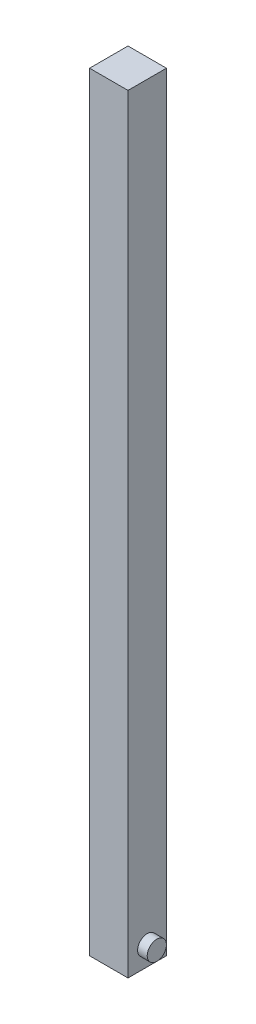
SolidWorks part; units mm, degrees
ref_plane "Front Plane" through (0, 0, 0) normal (0, 0, 1) x (1, 0, 0)
ref_plane "Top Plane" through (0, 0, 0) normal (0, 1, 0) x (1, 0, 0)
ref_plane "Right Plane" through (0, 0, 0) normal (1, 0, 0) x (0, 0, -1)
sketch "Sketch1" plane through (0, 0, 0) normal (0, 1, 0) x (1, 0, 0)
  line L1 (0, 0) -> (25.4, 0)
  line L2 (0, 0) -> (0, 25.4)
  line L3 (0, 25.4) -> (25.4, 25.4)
  line L4 (25.4, 0) -> (25.4, 25.4)
extrude "Boss-Extrude2" add sketch "Sketch1" along normal blind 508
sketch "Sketch3" plane through (25.4, 0, 0) normal (1, 0, 0) x (0, 0, -1)
  line L0 (0, 508) -> (25.4, 508) construction
  line L1 (0, 508) -> (0, 0) construction
  circle A0 centre (12.7, 12.7) radius 6.35
  dimension "D1" = 495.3
  dimension "D2" = 12.7
extrude "Boss-Extrude4" add sketch "Sketch3" along normal blind 6.35
